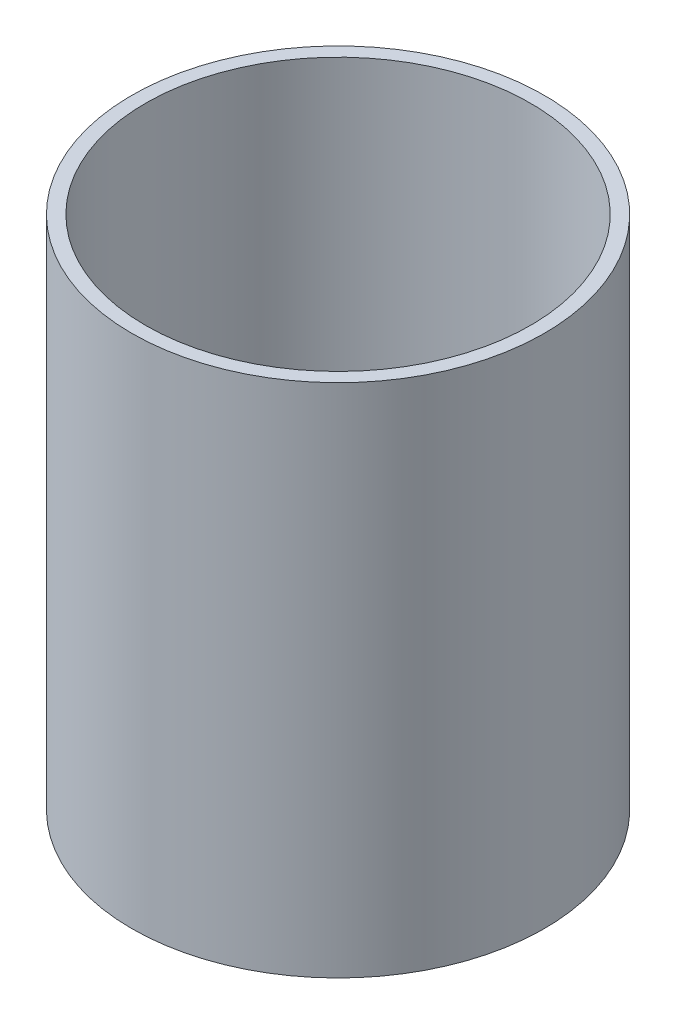
SolidWorks part; units mm, degrees
ref_plane "Front Plane" through (0, 0, 0) normal (0, 0, 1) x (1, 0, 0)
ref_plane "Top Plane" through (0, 0, 0) normal (0, 1, 0) x (1, 0, 0)
ref_plane "Right Plane" through (0, 0, 0) normal (1, 0, 0) x (0, 0, -1)
sketch "Sketch2" plane through (0, 0, 0) normal (0, 1, 0) x (1, 0, 0)
  circle A0 centre (0, 0) radius 6
  circle A1 centre (0, 0) radius 5.6
extrude "Boss-Extrude1" add sketch "Sketch2" along normal blind 15
